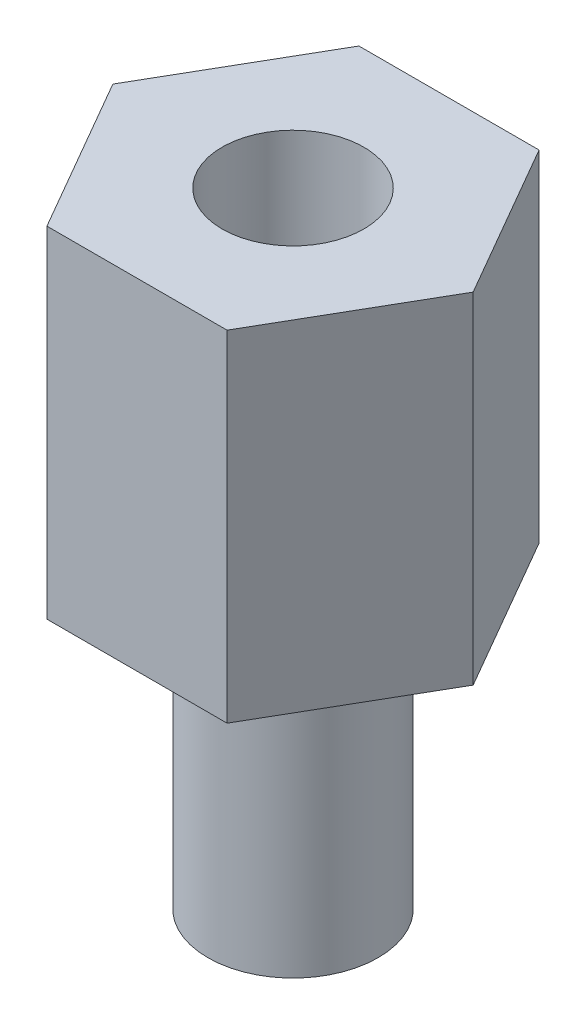
SolidWorks part; units mm, degrees
material "ABS"
ref_plane "Front Plane" through (0, 0, 0) normal (0, 0, 1) x (1, 0, 0)
ref_plane "Top Plane" through (0, 0, 0) normal (0, 1, 0) x (1, 0, 0)
ref_plane "Right Plane" through (0, 0, 0) normal (1, 0, 0) x (0, 0, -1)
sketch "Sketch1" plane through (0, 0, 0) normal (0, 1, 0) x (1, 0, 0)
  line L1 (1.5877, 2.75) -> (-1.5877, 2.75)
  line L2 (-1.5877, 2.75) -> (-3.1754, 0)
  line L3 (-3.1754, 0) -> (-1.5877, -2.75)
  line L4 (-1.5877, -2.75) -> (1.5877, -2.75)
  line L5 (1.5877, -2.75) -> (3.1754, 0)
  line L6 (3.1754, 0) -> (1.5877, 2.75)
  circle A0 centre (0, 0) radius 2.75 construction
  dimension "D1" = 5.5
extrude "Boss-Extrude1" add sketch "Sketch1" along normal blind 6
sketch "Sketch2" plane through (0, 0, 0) normal (0, -1, 0) x (1, 0, 0)
  circle A0 centre (0, 0) radius 1.5
  dimension "D1" = 3
extrude "Boss-Extrude2" add sketch "Sketch2" along normal blind 5
sketch "Sketch3" plane through (0, 6, 0) normal (0, 1, 0) x (1, 0, 0)
  point P0 (0, 0)
hole_wizard "M3x0.5 Tapped Hole1" positions "Sketch5" profile "Sketch6" tap size "M3x0.5" standard "ANSI Metric"
sketch "Sketch5" plane through (0, 6, 0) normal (0, 1, 0) x (1, 0, 0)
  point P0 (0, 0)
sketch "Sketch6" plane through (0, 6, 0) normal (1, 0, 0) x (0, 0, 1)
  line L0 (0, 0) -> (0, 6.2511)
  line L1 (0, 6.2511) -> (1.25, 5.5)
  line L2 (1.25, 5.5) -> (1.25, 0)
  line L5 (1.25, 0) -> (0, 0)
  line L10 (0, 6.2511) -> (-1.25, 5.5) construction
  line L11 (0, -6.35) -> (0, 107.95) construction
  dimension "Tap Drill Dia." = 2.5
  dimension "Tap Drill Depth" = 5.5
  dimension "Drill Angle" = 118
cosmetic thread "Hole Thread1" parameters "D1"=3.8, "D2"=3
